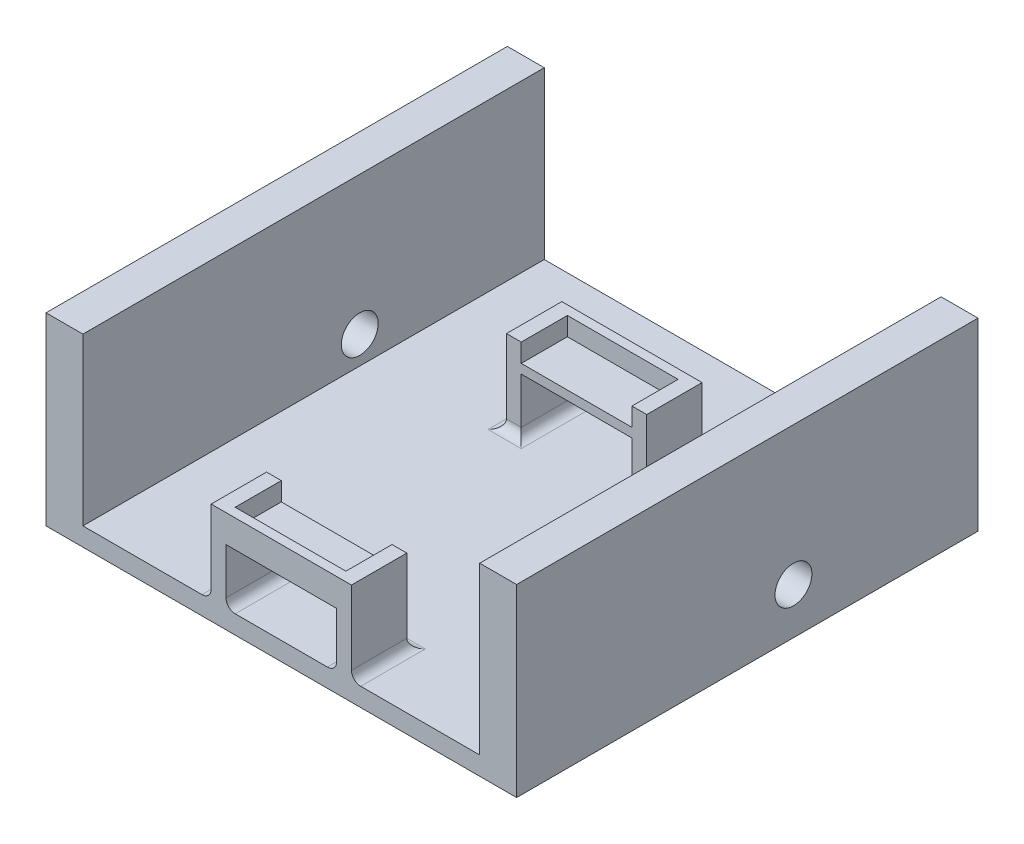
SolidWorks part; units mm, degrees
ref_plane "前基準面" through (0, 0, 0) normal (0, 0, 1) x (1, 0, 0)
ref_plane "上基準面" through (0, 0, 0) normal (0, 1, 0) x (1, 0, 0)
ref_plane "右基準面" through (0, 0, 0) normal (1, 0, 0) x (0, 0, -1)
sketch "草圖4" plane through (0, 0, 0) normal (0, 1, 0) x (1, 0, 0)
  line L1 (-127.5, 125) -> (127.5, 125)
  line L2 (-127.5, 125) -> (-127.5, -125)
  line L3 (-127.5, -125) -> (127.5, -125)
  line L4 (127.5, 125) -> (127.5, -125)
  line L5 (-127.5, 125) -> (127.5, -125) construction
  line L6 (-127.5, -125) -> (127.5, 125) construction
  point P0 (0, 0)
  dimension "D1" = 255
  dimension "D2" = 250
extrude "填料-伸長2" add sketch "草圖4" along normal blind 10
sketch "草圖7" plane through (0, 10, 0) normal (0, 1, 0) x (1, 0, 0)
  line L0 (-127.5, -125) -> (127.5, -125) construction
  line L1 (-127.5, 125) -> (-107.5, 125)
  line L2 (-127.5, 125) -> (-127.5, -125)
  line L3 (-127.5, -125) -> (-107.5, -125)
  line L4 (-107.5, 125) -> (-107.5, -125)
  line L5 (127.5, 125) -> (-127.5, 125) construction
  line L6 (127.5, -125) -> (107.5, -125)
  line L7 (127.5, -125) -> (127.5, 125)
  line L8 (127.5, 125) -> (107.5, 125)
  line L9 (107.5, -125) -> (107.5, 125)
  line L10 (0, 160.1697) -> (0, -166.2631) construction
  line L20 (42.5, -150) -> (-42.5, -150) construction
  line L21 (42.5, -150) -> (42.5, 110) construction
  line L22 (42.5, 110) -> (-42.5, 110) construction
  line L23 (-42.5, -150) -> (-42.5, 110) construction
  dimension "D1" = 20
  dimension "D2" = 20
  dimension "D4" = 260
  dimension "D5" = 85
extrude "填料-伸長3" add sketch "草圖7" along normal blind 90
sketch "草圖8" plane through (0, 0, 125) normal (0, 0, 1) x (1, 0, 0)
  line L0 (0, 114.0362) -> (0, -18.6102) construction
  line L1 (-30, 10) -> (-38, 10)
  line L2 (-107.5, 10) -> (107.5, 10) construction
  line L3 (-38, 10) -> (-38, 55)
  line L4 (-38, 55) -> (-30, 55)
  line L7 (-30, 40) -> (-30, 10)
  line L10 (38, 55) -> (30, 55)
  line L11 (38, 10) -> (38, 55)
  line L12 (30, 10) -> (38, 10)
  line L13 (30, 40) -> (30, 10)
  line L14 (30, 45) -> (30, 55)
  line L15 (-30, 45) -> (-30, 55)
  line L16 (30, 45) -> (-30, 45)
  line L17 (-30, 40) -> (30, 40)
  dimension "D1" = 60
  dimension "D2" = 8
  dimension "D3" = 60
  dimension "D4" = 10
  dimension "D5" = 45
  dimension "D6" = 30
  dimension "D7" = 5
extrude "填料-伸長4" add sketch "草圖8" against normal blind 30
sketch "草圖9" plane through (-127.5, 0, 0) normal (-1, 0, 0) x (0, 0, 1)
  line L0 (-125, 0) -> (125, 0) construction
  line L2 (-125, 100) -> (-125, 0) construction
  circle A0 centre (-25, 25) radius 10
  dimension "D1" = 20
  dimension "D2" = 25
  dimension "D3" = 100
extrude "除料-伸長1" cut sketch "草圖9" against normal up to next
mirror "鏡射1" about plane through (0, 0, 0) normal (1, 0, 0) of "除料-伸長1"
sketch "草圖11" plane through (0, 0, 125) normal (0, 0, 1) x (1, 0, 0)
  line L10 (0, 0) -> (0, 84.8358) construction
  line L11 (-127.5, 0) -> (127.5, 0) construction
  line L23 (-30, 45) -> (30, 45)
  line L24 (-30, 45) -> (-30, 55)
  line L25 (-30, 55) -> (30, 55)
  line L26 (30, 45) -> (30, 55)
extrude "填料-伸長6" add sketch "草圖11" against normal blind 5
fillet "圓角1" radius 5 6 edges at (38, 10, 110) (-38, 10, 110) (30, 10, 110) (-30, 10, 110) (-34, 10, 95) (34, 10, 95)
ref_plane "平面1" through (0, 0, 30) normal (0, 0, -1) x (-1, 0, 0)
mirror "鏡射2" about plane through (0, 0, 30) normal (0, 0, -1) of "填料-伸長6", "填料-伸長4", "圓角1"
